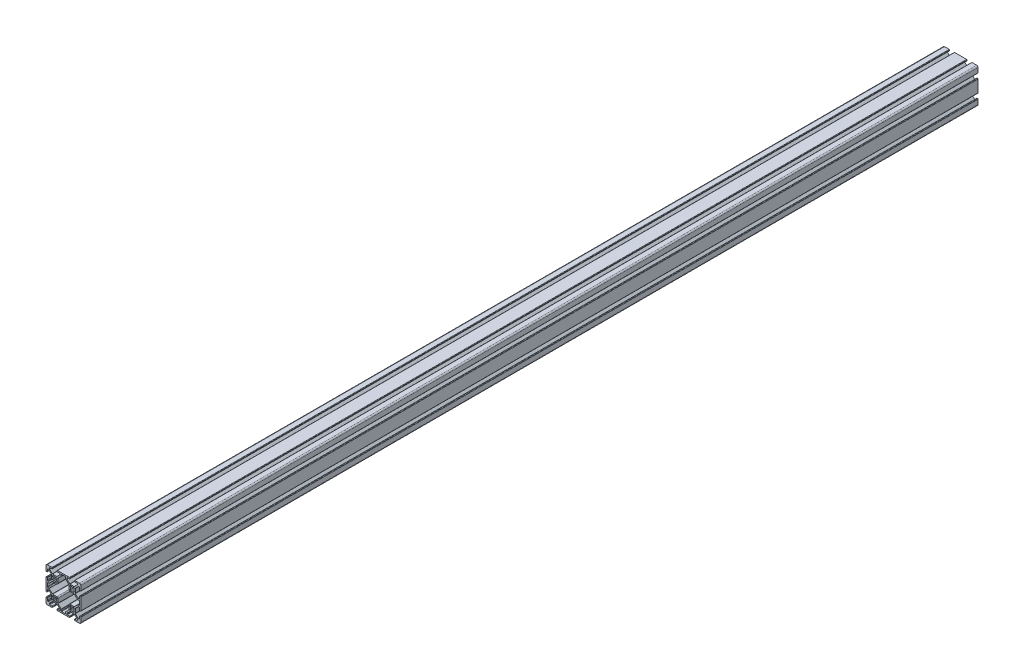
SolidWorks part; units mm, degrees
material "6061 Alloy"
ref_plane "Front Plane" through (0, 0, 0) normal (0, 0, 1) x (1, 0, 0)
ref_plane "Top Plane" through (0, 0, 0) normal (0, 1, 0) x (1, 0, 0)
ref_plane "Right Plane" through (0, 0, 0) normal (1, 0, 0) x (0, 0, -1)
sketch "Sketch1" plane through (0, 0, 0) normal (0, 0, 1) x (1, 0, 0)
  line L0 (-16.6492, -131.4291) -> (-16.8288, -131.2495)
  line L1 (-16.8288, -126.9997) -> (-16.6492, -126.8201)
  line L2 (-12.3994, -126.8201) -> (-12.2198, -126.9997)
  line L3 (-12.2198, -131.2495) -> (-12.3994, -131.4291)
  line L4 (-36.6492, -131.4291) -> (-36.8288, -131.2495)
  line L5 (-36.8288, -126.9997) -> (-36.6492, -126.8201)
  line L6 (-32.3994, -126.8201) -> (-32.2198, -126.9997)
  line L7 (-32.2198, -131.2495) -> (-32.3994, -131.4291)
  line L8 (-16.6492, -151.4291) -> (-16.8288, -151.2495)
  line L9 (-16.8288, -146.9997) -> (-16.6492, -146.8201)
  line L10 (-12.3994, -146.8201) -> (-12.2198, -146.9997)
  line L11 (-12.2198, -151.2495) -> (-12.3994, -151.4291)
  line L12 (-27.0293, -157.1166) -> (-27.0293, -155.7694)
  line L13 (-27.1781, -155.4102) -> (-30.7205, -151.8677)
  line L14 (-30.8693, -151.5085) -> (-30.8693, -146.6126)
  line L15 (-32.0123, -145.4696) -> (-36.9082, -145.4696)
  line L16 (-37.2674, -145.3208) -> (-40.8098, -141.7784)
  line L17 (-41.169, -141.6296) -> (-42.5163, -141.6296)
  line L18 (-43.0243, -141.1216) -> (-43.0243, -137.1276)
  line L19 (-42.5163, -136.6196) -> (-41.169, -136.6196)
  line L20 (-40.8098, -136.4708) -> (-37.2674, -132.9284)
  line L21 (-36.9082, -132.7796) -> (-32.0123, -132.7796)
  line L22 (-30.8693, -131.6366) -> (-30.8693, -126.7407)
  line L23 (-30.7205, -126.3815) -> (-27.1781, -122.8391)
  line L24 (-27.0293, -122.4798) -> (-27.0293, -121.1326)
  line L25 (-26.5213, -120.6246) -> (-22.5273, -120.6246)
  line L26 (-22.0193, -121.1326) -> (-22.0193, -122.4798)
  line L27 (-21.8705, -122.8391) -> (-18.3281, -126.3815)
  line L28 (-18.1793, -126.7407) -> (-18.1793, -131.6366)
  line L29 (-17.0363, -132.7796) -> (-12.1404, -132.7796)
  line L30 (-11.7812, -132.9284) -> (-8.2387, -136.4708)
  line L31 (-7.8795, -136.6196) -> (-6.5323, -136.6196)
  line L32 (-6.0243, -137.1276) -> (-6.0243, -141.1216)
  line L33 (-6.5323, -141.6296) -> (-7.8795, -141.6296)
  line L34 (-8.2387, -141.7784) -> (-11.7812, -145.3208)
  line L35 (-12.1404, -145.4696) -> (-17.0363, -145.4696)
  line L36 (-18.1793, -146.6126) -> (-18.1793, -151.5085)
  line L37 (-18.3281, -151.8677) -> (-21.8705, -155.4102)
  line L38 (-22.0193, -155.7694) -> (-22.0193, -157.1166)
  line L39 (-22.5273, -157.6246) -> (-26.5213, -157.6246)
  line L40 (-36.6492, -151.4291) -> (-36.8288, -151.2495)
  line L41 (-36.8288, -146.9997) -> (-36.6492, -146.8201)
  line L42 (-32.3994, -146.8201) -> (-32.2198, -146.9997)
  line L43 (-32.2198, -151.2495) -> (-32.3994, -151.4291)
  line L44 (-36.9082, -152.7796) -> (-32.1404, -152.7796)
  line L45 (-31.7812, -152.9284) -> (-28.6781, -156.0315)
  line L46 (-28.5293, -156.3907) -> (-28.5293, -157.1166)
  line L47 (-29.0373, -157.6246) -> (-31.3863, -157.6246)
  line L48 (-31.8943, -158.1326) -> (-31.8943, -158.6166)
  line L49 (-31.3863, -159.1246) -> (-17.6623, -159.1246)
  line L50 (-17.1543, -158.6166) -> (-17.1543, -158.1326)
  line L51 (-17.6623, -157.6246) -> (-20.0113, -157.6246)
  line L52 (-20.5193, -157.1166) -> (-20.5193, -156.3907)
  line L53 (-20.3705, -156.0315) -> (-17.2674, -152.9284)
  line L54 (-16.9082, -152.7796) -> (-12.1404, -152.7796)
  line L55 (-11.7812, -152.9284) -> (-8.6781, -156.0315)
  line L56 (-8.5293, -156.3907) -> (-8.5293, -157.1166)
  line L57 (-9.0373, -157.6246) -> (-11.3863, -157.6246)
  line L58 (-11.8943, -158.1326) -> (-11.8943, -158.6166)
  line L59 (-11.3863, -159.1246) -> (-6.0243, -159.1246)
  line L60 (-4.5243, -157.6246) -> (-4.5243, -152.2626)
  line L61 (-5.0323, -151.7546) -> (-5.5163, -151.7546)
  line L62 (-6.0243, -152.2626) -> (-6.0243, -154.6116)
  line L63 (-6.5323, -155.1196) -> (-7.2582, -155.1196)
  line L64 (-7.6174, -154.9708) -> (-10.7205, -151.8677)
  line L65 (-10.8693, -151.5085) -> (-10.8693, -146.7407)
  line L66 (-10.7205, -146.3815) -> (-7.6174, -143.2784)
  line L67 (-7.2582, -143.1296) -> (-6.5323, -143.1296)
  line L68 (-6.0243, -143.6376) -> (-6.0243, -145.9866)
  line L69 (-5.5163, -146.4946) -> (-5.0323, -146.4946)
  line L70 (-4.5243, -145.9866) -> (-4.5243, -132.2626)
  line L71 (-5.0323, -131.7546) -> (-5.5163, -131.7546)
  line L72 (-6.0243, -132.2626) -> (-6.0243, -134.6116)
  line L73 (-6.5323, -135.1196) -> (-7.2582, -135.1196)
  line L74 (-7.6174, -134.9708) -> (-10.7205, -131.8677)
  line L75 (-10.8693, -131.5085) -> (-10.8693, -126.7407)
  line L76 (-10.7205, -126.3815) -> (-7.6174, -123.2784)
  line L77 (-7.2582, -123.1296) -> (-6.5323, -123.1296)
  line L78 (-6.0243, -123.6376) -> (-6.0243, -125.9866)
  line L79 (-5.5163, -126.4946) -> (-5.0323, -126.4946)
  line L80 (-4.5243, -125.9866) -> (-4.5243, -120.6246)
  line L81 (-6.0243, -119.1246) -> (-11.3863, -119.1246)
  line L82 (-11.8943, -119.6326) -> (-11.8943, -120.1166)
  line L83 (-11.3863, -120.6246) -> (-9.0373, -120.6246)
  line L84 (-8.5293, -121.1326) -> (-8.5293, -121.8585)
  line L85 (-8.6781, -122.2177) -> (-11.7812, -125.3208)
  line L86 (-12.1404, -125.4696) -> (-16.9082, -125.4696)
  line L87 (-17.2674, -125.3208) -> (-20.3705, -122.2177)
  line L88 (-20.5193, -121.8585) -> (-20.5193, -121.1326)
  line L89 (-20.0113, -120.6246) -> (-17.6623, -120.6246)
  line L90 (-17.1543, -120.1166) -> (-17.1543, -119.6326)
  line L91 (-17.6623, -119.1246) -> (-31.3863, -119.1246)
  line L92 (-31.8943, -119.6326) -> (-31.8943, -120.1166)
  line L93 (-31.3863, -120.6246) -> (-29.0373, -120.6246)
  line L94 (-28.5293, -121.1326) -> (-28.5293, -121.8585)
  line L95 (-28.6781, -122.2177) -> (-31.7812, -125.3208)
  line L96 (-32.1404, -125.4696) -> (-36.9082, -125.4696)
  line L97 (-37.2674, -125.3208) -> (-40.3705, -122.2177)
  line L98 (-40.5193, -121.8585) -> (-40.5193, -121.1326)
  line L99 (-40.0113, -120.6246) -> (-37.6623, -120.6246)
  line L100 (-37.1543, -120.1166) -> (-37.1543, -119.6326)
  line L101 (-37.6623, -119.1246) -> (-43.0243, -119.1246)
  line L102 (-44.5243, -120.6246) -> (-44.5243, -125.9866)
  line L103 (-44.0163, -126.4946) -> (-43.5323, -126.4946)
  line L104 (-43.0243, -125.9866) -> (-43.0243, -123.6376)
  line L105 (-42.5163, -123.1296) -> (-41.7904, -123.1296)
  line L106 (-41.4312, -123.2784) -> (-38.3281, -126.3815)
  line L107 (-38.1793, -126.7407) -> (-38.1793, -131.5085)
  line L108 (-38.3281, -131.8677) -> (-41.4312, -134.9708)
  line L109 (-41.7904, -135.1196) -> (-42.5163, -135.1196)
  line L110 (-43.0243, -134.6116) -> (-43.0243, -132.2626)
  line L111 (-43.5323, -131.7546) -> (-44.0163, -131.7546)
  line L112 (-44.5243, -132.2626) -> (-44.5243, -145.9866)
  line L113 (-44.0163, -146.4946) -> (-43.5323, -146.4946)
  line L114 (-43.0243, -145.9866) -> (-43.0243, -143.6376)
  line L115 (-42.5163, -143.1296) -> (-41.7904, -143.1296)
  line L116 (-41.4312, -143.2784) -> (-38.3281, -146.3815)
  line L117 (-38.1793, -146.7407) -> (-38.1793, -151.5085)
  line L118 (-38.3281, -151.8677) -> (-41.4312, -154.9708)
  line L119 (-41.7904, -155.1196) -> (-42.5163, -155.1196)
  line L120 (-43.0243, -154.6116) -> (-43.0243, -152.2626)
  line L121 (-43.5323, -151.7546) -> (-44.0163, -151.7546)
  line L122 (-44.5243, -152.2626) -> (-44.5243, -157.6246)
  line L123 (-43.0243, -159.1246) -> (-37.6623, -159.1246)
  line L124 (-37.1543, -158.6166) -> (-37.1543, -158.1326)
  line L125 (-37.6623, -157.6246) -> (-40.0113, -157.6246)
  line L126 (-40.5193, -157.1166) -> (-40.5193, -156.3907)
  line L127 (-40.3705, -156.0315) -> (-37.2674, -152.9284)
  arc A0 (-16.4594, -129.9286) -> (-16.8288, -131.2495) centre (-16.2723, -130.693) ccw
  arc A1 (-16.4594, -128.3206) -> (-16.4594, -129.9286) centre (-14.5243, -129.1246) ccw
  arc A2 (-16.8288, -126.9997) -> (-16.4594, -128.3206) centre (-16.2723, -127.5562) ccw
  arc A3 (-15.3283, -127.1895) -> (-16.6492, -126.8201) centre (-16.0927, -127.3766) ccw
  arc A4 (-13.7203, -127.1895) -> (-15.3283, -127.1895) centre (-14.5243, -129.1246) ccw
  arc A5 (-12.3994, -126.8201) -> (-13.7203, -127.1895) centre (-12.9559, -127.3766) ccw
  arc A6 (-12.5892, -128.3206) -> (-12.2198, -126.9997) centre (-12.7763, -127.5562) ccw
  arc A7 (-12.5892, -129.9286) -> (-12.5892, -128.3206) centre (-14.5243, -129.1246) ccw
  arc A8 (-12.2198, -131.2495) -> (-12.5892, -129.9286) centre (-12.7763, -130.693) ccw
  arc A9 (-13.7203, -131.0597) -> (-12.3994, -131.4291) centre (-12.9559, -130.8726) ccw
  arc A10 (-15.3283, -131.0597) -> (-13.7203, -131.0597) centre (-14.5243, -129.1246) ccw
  arc A11 (-16.6492, -131.4291) -> (-15.3283, -131.0597) centre (-16.0927, -130.8726) ccw
  arc A12 (-36.4594, -129.9286) -> (-36.8288, -131.2495) centre (-36.2723, -130.693) ccw
  arc A13 (-36.4594, -128.3206) -> (-36.4594, -129.9286) centre (-34.5243, -129.1246) ccw
  arc A14 (-36.8288, -126.9997) -> (-36.4594, -128.3206) centre (-36.2723, -127.5562) ccw
  arc A15 (-35.3283, -127.1895) -> (-36.6492, -126.8201) centre (-36.0927, -127.3766) ccw
  arc A16 (-33.7203, -127.1895) -> (-35.3283, -127.1895) centre (-34.5243, -129.1246) ccw
  arc A17 (-32.3994, -126.8201) -> (-33.7203, -127.1895) centre (-32.9559, -127.3766) ccw
  arc A18 (-32.5892, -128.3206) -> (-32.2198, -126.9997) centre (-32.7763, -127.5562) ccw
  arc A19 (-32.5892, -129.9286) -> (-32.5892, -128.3206) centre (-34.5243, -129.1246) ccw
  arc A20 (-32.2198, -131.2495) -> (-32.5892, -129.9286) centre (-32.7763, -130.693) ccw
  arc A21 (-33.7203, -131.0597) -> (-32.3994, -131.4291) centre (-32.9559, -130.8726) ccw
  arc A22 (-35.3283, -131.0597) -> (-33.7203, -131.0597) centre (-34.5243, -129.1246) ccw
  arc A23 (-36.6492, -131.4291) -> (-35.3283, -131.0597) centre (-36.0927, -130.8726) ccw
  arc A24 (-16.4594, -149.9286) -> (-16.8288, -151.2495) centre (-16.2723, -150.693) ccw
  arc A25 (-16.4594, -148.3206) -> (-16.4594, -149.9286) centre (-14.5243, -149.1246) ccw
  arc A26 (-16.8288, -146.9997) -> (-16.4594, -148.3206) centre (-16.2723, -147.5562) ccw
  arc A27 (-15.3283, -147.1895) -> (-16.6492, -146.8201) centre (-16.0927, -147.3766) ccw
  arc A28 (-13.7203, -147.1895) -> (-15.3283, -147.1895) centre (-14.5243, -149.1246) ccw
  arc A29 (-12.3994, -146.8201) -> (-13.7203, -147.1895) centre (-12.9559, -147.3766) ccw
  arc A30 (-12.5892, -148.3206) -> (-12.2198, -146.9997) centre (-12.7763, -147.5562) ccw
  arc A31 (-12.5892, -149.9286) -> (-12.5892, -148.3206) centre (-14.5243, -149.1246) ccw
  arc A32 (-12.2198, -151.2495) -> (-12.5892, -149.9286) centre (-12.7763, -150.693) ccw
  arc A33 (-13.7203, -151.0597) -> (-12.3994, -151.4291) centre (-12.9559, -150.8726) ccw
  arc A34 (-15.3283, -151.0597) -> (-13.7203, -151.0597) centre (-14.5243, -149.1246) ccw
  arc A35 (-16.6492, -151.4291) -> (-15.3283, -151.0597) centre (-16.0927, -150.8726) ccw
  arc A36 (-27.0293, -157.1166) -> (-26.5213, -157.6246) centre (-26.5213, -157.1166) ccw
  arc A37 (-27.0293, -155.7694) -> (-27.1781, -155.4102) centre (-27.5373, -155.7694) ccw
  arc A38 (-30.8693, -151.5085) -> (-30.7205, -151.8677) centre (-30.3613, -151.5085) ccw
  arc A39 (-30.8693, -146.6126) -> (-32.0123, -145.4696) centre (-32.0123, -146.6126) ccw
  arc A40 (-37.2674, -145.3208) -> (-36.9082, -145.4696) centre (-36.9082, -144.9616) ccw
  arc A41 (-40.8098, -141.7784) -> (-41.169, -141.6296) centre (-41.169, -142.1376) ccw
  arc A42 (-43.0243, -141.1216) -> (-42.5163, -141.6296) centre (-42.5163, -141.1216) ccw
  arc A43 (-42.5163, -136.6196) -> (-43.0243, -137.1276) centre (-42.5163, -137.1276) ccw
  arc A44 (-41.169, -136.6196) -> (-40.8098, -136.4708) centre (-41.169, -136.1116) ccw
  arc A45 (-36.9082, -132.7796) -> (-37.2674, -132.9284) centre (-36.9082, -133.2876) ccw
  arc A46 (-32.0123, -132.7796) -> (-30.8693, -131.6366) centre (-32.0123, -131.6366) ccw
  arc A47 (-30.7205, -126.3815) -> (-30.8693, -126.7407) centre (-30.3613, -126.7407) ccw
  arc A48 (-27.1781, -122.8391) -> (-27.0293, -122.4798) centre (-27.5373, -122.4798) ccw
  arc A49 (-26.5213, -120.6246) -> (-27.0293, -121.1326) centre (-26.5213, -121.1326) ccw
  arc A50 (-22.0193, -121.1326) -> (-22.5273, -120.6246) centre (-22.5273, -121.1326) ccw
  arc A51 (-22.0193, -122.4798) -> (-21.8705, -122.8391) centre (-21.5113, -122.4798) ccw
  arc A52 (-18.1793, -126.7407) -> (-18.3281, -126.3815) centre (-18.6873, -126.7407) ccw
  arc A53 (-18.1793, -131.6366) -> (-17.0363, -132.7796) centre (-17.0363, -131.6366) ccw
  arc A54 (-11.7812, -132.9284) -> (-12.1404, -132.7796) centre (-12.1404, -133.2876) ccw
  arc A55 (-8.2387, -136.4708) -> (-7.8795, -136.6196) centre (-7.8795, -136.1116) ccw
  arc A56 (-6.0243, -137.1276) -> (-6.5323, -136.6196) centre (-6.5323, -137.1276) ccw
  arc A57 (-6.5323, -141.6296) -> (-6.0243, -141.1216) centre (-6.5323, -141.1216) ccw
  arc A58 (-7.8795, -141.6296) -> (-8.2387, -141.7784) centre (-7.8795, -142.1376) ccw
  arc A59 (-12.1404, -145.4696) -> (-11.7812, -145.3208) centre (-12.1404, -144.9616) ccw
  arc A60 (-17.0363, -145.4696) -> (-18.1793, -146.6126) centre (-17.0363, -146.6126) ccw
  arc A61 (-18.3281, -151.8677) -> (-18.1793, -151.5085) centre (-18.6873, -151.5085) ccw
  arc A62 (-21.8705, -155.4102) -> (-22.0193, -155.7694) centre (-21.5113, -155.7694) ccw
  arc A63 (-22.5273, -157.6246) -> (-22.0193, -157.1166) centre (-22.5273, -157.1166) ccw
  arc A64 (-36.4594, -149.9286) -> (-36.8288, -151.2495) centre (-36.2723, -150.693) ccw
  arc A65 (-36.4594, -148.3206) -> (-36.4594, -149.9286) centre (-34.5243, -149.1246) ccw
  arc A66 (-36.8288, -146.9997) -> (-36.4594, -148.3206) centre (-36.2723, -147.5562) ccw
  arc A67 (-35.3283, -147.1895) -> (-36.6492, -146.8201) centre (-36.0927, -147.3766) ccw
  arc A68 (-33.7203, -147.1895) -> (-35.3283, -147.1895) centre (-34.5243, -149.1246) ccw
  arc A69 (-32.3994, -146.8201) -> (-33.7203, -147.1895) centre (-32.9559, -147.3766) ccw
  arc A70 (-32.5892, -148.3206) -> (-32.2198, -146.9997) centre (-32.7763, -147.5562) ccw
  arc A71 (-32.5892, -149.9286) -> (-32.5892, -148.3206) centre (-34.5243, -149.1246) ccw
  arc A72 (-32.2198, -151.2495) -> (-32.5892, -149.9286) centre (-32.7763, -150.693) ccw
  arc A73 (-33.7203, -151.0597) -> (-32.3994, -151.4291) centre (-32.9559, -150.8726) ccw
  arc A74 (-35.3283, -151.0597) -> (-33.7203, -151.0597) centre (-34.5243, -149.1246) ccw
  arc A75 (-36.6492, -151.4291) -> (-35.3283, -151.0597) centre (-36.0927, -150.8726) ccw
  arc A76 (-36.9082, -152.7796) -> (-37.2674, -152.9284) centre (-36.9082, -153.2876) ccw
  arc A77 (-31.7812, -152.9284) -> (-32.1404, -152.7796) centre (-32.1404, -153.2876) ccw
  arc A78 (-28.5293, -156.3907) -> (-28.6781, -156.0315) centre (-29.0373, -156.3907) ccw
  arc A79 (-29.0373, -157.6246) -> (-28.5293, -157.1166) centre (-29.0373, -157.1166) ccw
  arc A80 (-31.3863, -157.6246) -> (-31.8943, -158.1326) centre (-31.3863, -158.1326) ccw
  arc A81 (-31.8943, -158.6166) -> (-31.3863, -159.1246) centre (-31.3863, -158.6166) ccw
  arc A82 (-17.6623, -159.1246) -> (-17.1543, -158.6166) centre (-17.6623, -158.6166) ccw
  arc A83 (-17.1543, -158.1326) -> (-17.6623, -157.6246) centre (-17.6623, -158.1326) ccw
  arc A84 (-20.5193, -157.1166) -> (-20.0113, -157.6246) centre (-20.0113, -157.1166) ccw
  arc A85 (-20.3705, -156.0315) -> (-20.5193, -156.3907) centre (-20.0113, -156.3907) ccw
  arc A86 (-16.9082, -152.7796) -> (-17.2674, -152.9284) centre (-16.9082, -153.2876) ccw
  arc A87 (-11.7812, -152.9284) -> (-12.1404, -152.7796) centre (-12.1404, -153.2876) ccw
  arc A88 (-8.5293, -156.3907) -> (-8.6781, -156.0315) centre (-9.0373, -156.3907) ccw
  arc A89 (-9.0373, -157.6246) -> (-8.5293, -157.1166) centre (-9.0373, -157.1166) ccw
  arc A90 (-11.3863, -157.6246) -> (-11.8943, -158.1326) centre (-11.3863, -158.1326) ccw
  arc A91 (-11.8943, -158.6166) -> (-11.3863, -159.1246) centre (-11.3863, -158.6166) ccw
  arc A92 (-6.0243, -159.1246) -> (-4.5243, -157.6246) centre (-6.0243, -157.6246) ccw
  arc A93 (-4.5243, -152.2626) -> (-5.0323, -151.7546) centre (-5.0323, -152.2626) ccw
  arc A94 (-5.5163, -151.7546) -> (-6.0243, -152.2626) centre (-5.5163, -152.2626) ccw
  arc A95 (-6.5323, -155.1196) -> (-6.0243, -154.6116) centre (-6.5323, -154.6116) ccw
  arc A96 (-7.6174, -154.9708) -> (-7.2582, -155.1196) centre (-7.2582, -154.6116) ccw
  arc A97 (-10.8693, -151.5085) -> (-10.7205, -151.8677) centre (-10.3613, -151.5085) ccw
  arc A98 (-10.7205, -146.3815) -> (-10.8693, -146.7407) centre (-10.3613, -146.7407) ccw
  arc A99 (-7.2582, -143.1296) -> (-7.6174, -143.2784) centre (-7.2582, -143.6376) ccw
  arc A100 (-6.0243, -143.6376) -> (-6.5323, -143.1296) centre (-6.5323, -143.6376) ccw
  arc A101 (-6.0243, -145.9866) -> (-5.5163, -146.4946) centre (-5.5163, -145.9866) ccw
  arc A102 (-5.0323, -146.4946) -> (-4.5243, -145.9866) centre (-5.0323, -145.9866) ccw
  arc A103 (-4.5243, -132.2626) -> (-5.0323, -131.7546) centre (-5.0323, -132.2626) ccw
  arc A104 (-5.5163, -131.7546) -> (-6.0243, -132.2626) centre (-5.5163, -132.2626) ccw
  arc A105 (-6.5323, -135.1196) -> (-6.0243, -134.6116) centre (-6.5323, -134.6116) ccw
  arc A106 (-7.6174, -134.9708) -> (-7.2582, -135.1196) centre (-7.2582, -134.6116) ccw
  arc A107 (-10.8693, -131.5085) -> (-10.7205, -131.8677) centre (-10.3613, -131.5085) ccw
  arc A108 (-10.7205, -126.3815) -> (-10.8693, -126.7407) centre (-10.3613, -126.7407) ccw
  arc A109 (-7.2582, -123.1296) -> (-7.6174, -123.2784) centre (-7.2582, -123.6376) ccw
  arc A110 (-6.0243, -123.6376) -> (-6.5323, -123.1296) centre (-6.5323, -123.6376) ccw
  arc A111 (-6.0243, -125.9866) -> (-5.5163, -126.4946) centre (-5.5163, -125.9866) ccw
  arc A112 (-5.0323, -126.4946) -> (-4.5243, -125.9866) centre (-5.0323, -125.9866) ccw
  arc A113 (-4.5243, -120.6246) -> (-6.0243, -119.1246) centre (-6.0243, -120.6246) ccw
  arc A114 (-11.3863, -119.1246) -> (-11.8943, -119.6326) centre (-11.3863, -119.6326) ccw
  arc A115 (-11.8943, -120.1166) -> (-11.3863, -120.6246) centre (-11.3863, -120.1166) ccw
  arc A116 (-8.5293, -121.1326) -> (-9.0373, -120.6246) centre (-9.0373, -121.1326) ccw
  arc A117 (-8.6781, -122.2177) -> (-8.5293, -121.8585) centre (-9.0373, -121.8585) ccw
  arc A118 (-12.1404, -125.4696) -> (-11.7812, -125.3208) centre (-12.1404, -124.9616) ccw
  arc A119 (-17.2674, -125.3208) -> (-16.9082, -125.4696) centre (-16.9082, -124.9616) ccw
  arc A120 (-20.5193, -121.8585) -> (-20.3705, -122.2177) centre (-20.0113, -121.8585) ccw
  arc A121 (-20.0113, -120.6246) -> (-20.5193, -121.1326) centre (-20.0113, -121.1326) ccw
  arc A122 (-17.6623, -120.6246) -> (-17.1543, -120.1166) centre (-17.6623, -120.1166) ccw
  arc A123 (-17.1543, -119.6326) -> (-17.6623, -119.1246) centre (-17.6623, -119.6326) ccw
  arc A124 (-31.3863, -119.1246) -> (-31.8943, -119.6326) centre (-31.3863, -119.6326) ccw
  arc A125 (-31.8943, -120.1166) -> (-31.3863, -120.6246) centre (-31.3863, -120.1166) ccw
  arc A126 (-28.5293, -121.1326) -> (-29.0373, -120.6246) centre (-29.0373, -121.1326) ccw
  arc A127 (-28.6781, -122.2177) -> (-28.5293, -121.8585) centre (-29.0373, -121.8585) ccw
  arc A128 (-32.1404, -125.4696) -> (-31.7812, -125.3208) centre (-32.1404, -124.9616) ccw
  arc A129 (-37.2674, -125.3208) -> (-36.9082, -125.4696) centre (-36.9082, -124.9616) ccw
  arc A130 (-40.5193, -121.8585) -> (-40.3705, -122.2177) centre (-40.0113, -121.8585) ccw
  arc A131 (-40.0113, -120.6246) -> (-40.5193, -121.1326) centre (-40.0113, -121.1326) ccw
  arc A132 (-37.6623, -120.6246) -> (-37.1543, -120.1166) centre (-37.6623, -120.1166) ccw
  arc A133 (-37.1543, -119.6326) -> (-37.6623, -119.1246) centre (-37.6623, -119.6326) ccw
  arc A134 (-43.0243, -119.1246) -> (-44.5243, -120.6246) centre (-43.0243, -120.6246) ccw
  arc A135 (-44.5243, -125.9866) -> (-44.0163, -126.4946) centre (-44.0163, -125.9866) ccw
  arc A136 (-43.5323, -126.4946) -> (-43.0243, -125.9866) centre (-43.5323, -125.9866) ccw
  arc A137 (-42.5163, -123.1296) -> (-43.0243, -123.6376) centre (-42.5163, -123.6376) ccw
  arc A138 (-41.4312, -123.2784) -> (-41.7904, -123.1296) centre (-41.7904, -123.6376) ccw
  arc A139 (-38.1793, -126.7407) -> (-38.3281, -126.3815) centre (-38.6873, -126.7407) ccw
  arc A140 (-38.3281, -131.8677) -> (-38.1793, -131.5085) centre (-38.6873, -131.5085) ccw
  arc A141 (-41.7904, -135.1196) -> (-41.4312, -134.9708) centre (-41.7904, -134.6116) ccw
  arc A142 (-43.0243, -134.6116) -> (-42.5163, -135.1196) centre (-42.5163, -134.6116) ccw
  arc A143 (-43.0243, -132.2626) -> (-43.5323, -131.7546) centre (-43.5323, -132.2626) ccw
  arc A144 (-44.0163, -131.7546) -> (-44.5243, -132.2626) centre (-44.0163, -132.2626) ccw
  arc A145 (-44.5243, -145.9866) -> (-44.0163, -146.4946) centre (-44.0163, -145.9866) ccw
  arc A146 (-43.5323, -146.4946) -> (-43.0243, -145.9866) centre (-43.5323, -145.9866) ccw
  arc A147 (-42.5163, -143.1296) -> (-43.0243, -143.6376) centre (-42.5163, -143.6376) ccw
  arc A148 (-41.4312, -143.2784) -> (-41.7904, -143.1296) centre (-41.7904, -143.6376) ccw
  arc A149 (-38.1793, -146.7407) -> (-38.3281, -146.3815) centre (-38.6873, -146.7407) ccw
  arc A150 (-38.3281, -151.8677) -> (-38.1793, -151.5085) centre (-38.6873, -151.5085) ccw
  arc A151 (-41.7904, -155.1196) -> (-41.4312, -154.9708) centre (-41.7904, -154.6116) ccw
  arc A152 (-43.0243, -154.6116) -> (-42.5163, -155.1196) centre (-42.5163, -154.6116) ccw
  arc A153 (-43.0243, -152.2626) -> (-43.5323, -151.7546) centre (-43.5323, -152.2626) ccw
  arc A154 (-44.0163, -151.7546) -> (-44.5243, -152.2626) centre (-44.0163, -152.2626) ccw
  arc A155 (-44.5243, -157.6246) -> (-43.0243, -159.1246) centre (-43.0243, -157.6246) ccw
  arc A156 (-37.6623, -159.1246) -> (-37.1543, -158.6166) centre (-37.6623, -158.6166) ccw
  arc A157 (-37.1543, -158.1326) -> (-37.6623, -157.6246) centre (-37.6623, -158.1326) ccw
  arc A158 (-40.5193, -157.1166) -> (-40.0113, -157.6246) centre (-40.0113, -157.1166) ccw
  arc A159 (-40.3705, -156.0315) -> (-40.5193, -156.3907) centre (-40.0113, -156.3907) ccw
extrude "Extrude1" add sketch "Sketch1" along normal blind 1031.698
